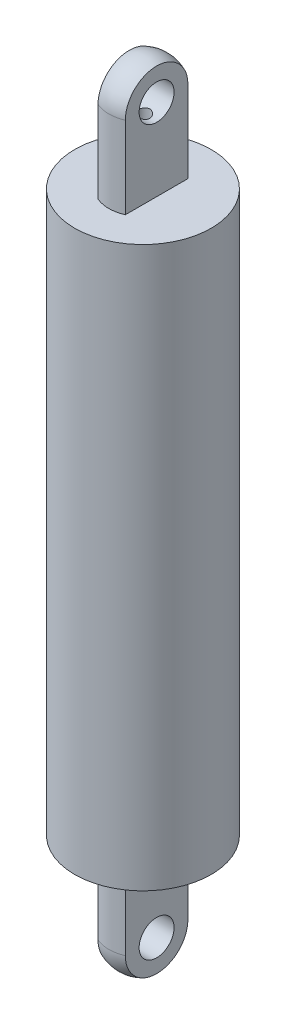
SolidWorks part; units mm, degrees
ref_plane "Front Plane" through (0, 0, 0) normal (0, 0, 1) x (1, 0, 0)
ref_plane "Top Plane" through (0, 0, 0) normal (0, 1, 0) x (1, 0, 0)
ref_plane "Right Plane" through (0, 0, 0) normal (1, 0, 0) x (0, 0, -1)
sketch "Sketch1" plane through (0, 0, 0) normal (1, 0, 0) x (0, 0, -1)
  line L0 (-6.35, 26.035) -> (-6.35, -26.035)
  line L1 (0, 33.655) -> (0, -33.655) construction
  line L2 (-3.175, 33.655) -> (-3.175, 26.035)
  line L3 (-3.175, 26.035) -> (-6.35, 26.035)
  line L4 (0, 36.83) -> (0, 33.655) construction
  line L5 (55, 0) -> (-55, 0) construction
  line L6 (-3.175, -26.035) -> (-6.35, -26.035)
  line L7 (-3.175, -33.655) -> (-3.175, -26.035)
  arc A0 (0, 35.282) -> (0, 32.028) centre (0, 33.655) ccw
  arc A1 (0, 36.83) -> (-3.175, 33.655) centre (0, 33.655) ccw
  arc A2 (0, -36.83) -> (-3.175, -33.655) centre (0, -33.655) cw
  arc A3 (0, -35.282) -> (0, -32.028) centre (0, -33.655) cw
  point P2 (-6.35, 0)
  point P6 (0, 0)
  dimension "D3" = 3.254
  dimension "D4" = 6.35
  dimension "D1" = 67.31
  dimension "D2" = 6.35
  dimension "D5" = 7.62
revolve "Revolve-Thin1" add sketch "Sketch1" angle 360 about L1
sketch "Sketch3" plane through (0, 26.035, 0) normal (0, 1, 0) x (1, 0, 0)
  line L1 (1.27, -3.81) -> (-1.27, -3.81) construction
  line L2 (1.27, -3.81) -> (1.27, 3.81)
  line L3 (1.27, 3.81) -> (-1.27, 3.81) construction
  line L4 (-1.27, -3.81) -> (-1.27, 3.81)
  line L5 (1.27, -3.81) -> (-1.27, 3.81) construction
  line L6 (1.27, 3.81) -> (-1.27, -3.81) construction
  line L7 (-1.27, 3.81) -> (-3.81, 3.81)
  line L8 (-1.27, 3.81) -> (-1.27, -3.81)
  line L9 (-1.27, -3.81) -> (-3.81, -3.81)
  line L10 (-3.81, 3.81) -> (-3.81, -3.81)
  line L11 (1.27, 3.81) -> (3.81, 3.81)
  line L12 (1.27, 3.81) -> (1.27, -3.81)
  line L13 (1.27, -3.81) -> (3.81, -3.81)
  line L14 (3.81, 3.81) -> (3.81, -3.81)
  point P0 (0, 0)
  circle M9 centre (0, 0) radius 3.175
  dimension "D1" = 2.54
  dimension "D2" = 7.62
  dimension "D3" = 2.54
extrude "Cut-Extrude2" cut sketch "Sketch3" along normal through all contours L4 M9 | L2 M9
mirror "Mirror1" about plane through (0, 0, 0) normal (0, 1, 0) of "Cut-Extrude2"
sketch "Sketch4" plane through (1.27, 0, 0) normal (1, 0, 0) x (0, 0, -1)
  line L0 (0, 55) -> (0, -55) construction
  circle A0 centre (0, 33.655) radius 1.627
  circle A1 centre (0, -33.655) radius 1.627
  arc A3 (2.9099, 33.655) -> (-2.9099, 33.655) centre (0, 33.655) ccw construction
  arc A4 (-2.9099, -33.655) -> (2.9099, -33.655) centre (0, -33.655) ccw construction
  dimension "D1" = 3.254
extrude "Cut-Extrude3" cut sketch "Sketch4" against normal through all
